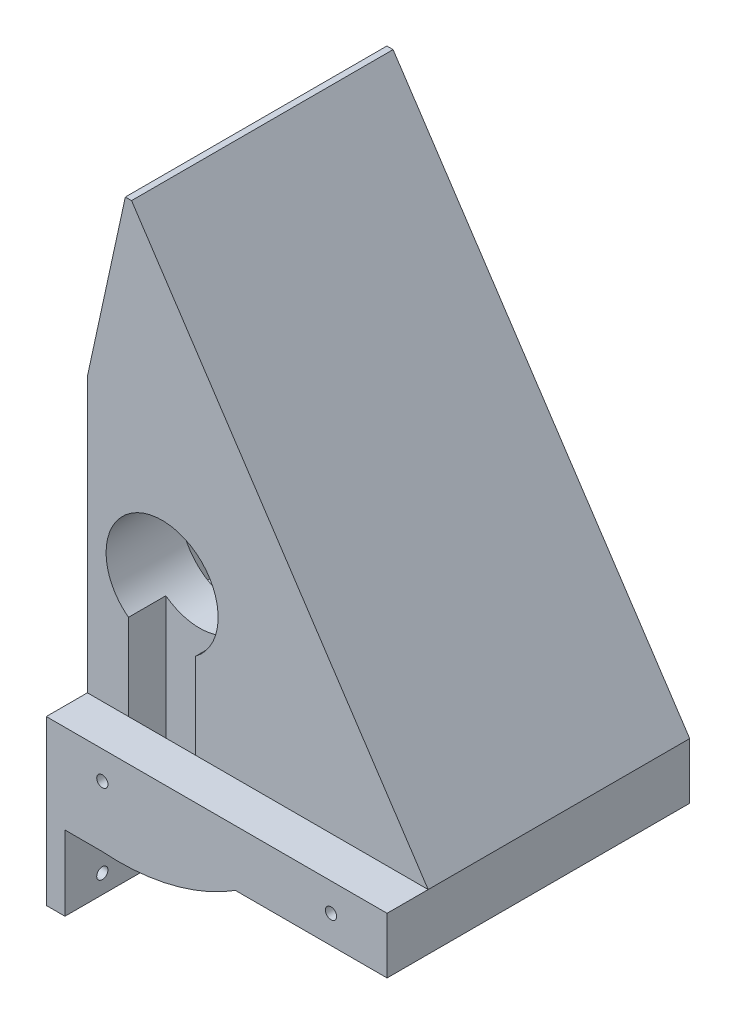
SolidWorks part; units mm, degrees
ref_plane "前视基准面" through (0, 0, 0) normal (0, 0, 1) x (1, 0, 0)
ref_plane "上视基准面" through (0, 0, 0) normal (0, 1, 0) x (1, 0, 0)
ref_plane "右视基准面" through (0, 0, 0) normal (1, 0, 0) x (0, 0, -1)
sketch "草图1" plane through (0, 0, 0) normal (1, 0, 0) x (0, 0, -1)
  line L0 (135, 0) -> (135, -170) construction
  line L1 (0, 0) -> (270, 0)
  line L2 (0, 0) -> (0, -100.2828)
  line L4 (270, 0) -> (270, -100.2828)
  line L5 (38.49, -136.6392) -> (62.3511, -70.3586) construction
  line L6 (21.17, -130.404) -> (127.5448, -168.6989) construction
  line L7 (142.4552, -168.6989) -> (248.83, -130.404) construction
  line L8 (58.2053, -81.8746) -> (-5.8219, -81.8746) construction
  line L9 (58.2053, -81.8746) -> (5.8219, -118.6911) construction
  line L10 (127.5448, -168.6989) -> (21.17, -130.404)
  line L11 (142.4552, -168.6989) -> (248.83, -130.404)
  line L12 (105.5031, -160.7639) -> (135, -78.8281) construction
  line L13 (135, -78.8281) -> (164.4969, -160.7639) construction
  arc A0 (0, -100.2828) -> (21.17, -130.404) centre (32.0136, -100.2828) ccw
  arc A1 (127.5448, -168.6989) -> (142.4552, -168.6989) centre (135, -147.9899) ccw
  arc A2 (270, -100.2828) -> (248.83, -130.404) centre (237.9864, -100.2828) cw
  dimension "D2" = 44.0202
  dimension "D3" = 170
  dimension "D1" = 270
  dimension "D4" = 32.0136
  dimension "D5" = 109.799
  dimension "D6" = 109.799
extrude "凸台-拉伸1" add sketch "草图1" along normal blind 30
sketch "草图2" plane through (30, 0, 0) normal (1, 0, 0) x (0, 0, -1)
  line L0 (135, 0) -> (135, -170) construction
  line L1 (270, 0) -> (0, 0) construction
  line L2 (135, -14.9009) -> (165, -14.9009) construction
  line L3 (165, 0) -> (165, -160.5828)
  line L4 (105, 0) -> (105, -160.5828)
  line L8 (0, 0) -> (0, -100.2828)
  line L9 (21.17, -130.404) -> (127.5448, -168.6989)
  line L10 (142.4552, -168.6989) -> (248.83, -130.404)
  line L11 (270, -100.2828) -> (270, 0)
  line L12 (270, 0) -> (0, 0)
  line L13 (0, 0) -> (0, -100.2828)
  line L14 (21.17, -130.404) -> (127.5448, -168.6989)
  line L15 (142.4552, -168.6989) -> (248.83, -130.404)
  line L16 (270, -100.2828) -> (270, 0)
  line L17 (270, 0) -> (0, 0)
  arc A0 (127.5448, -168.6989) -> (142.4552, -168.6989) centre (135, -147.9899) ccw construction
  arc A4 (0, -100.2828) -> (21.17, -130.404) centre (32.0136, -100.2828) ccw
  arc A5 (127.5448, -168.6989) -> (142.4552, -168.6989) centre (135, -147.9899) ccw
  arc A6 (248.83, -130.404) -> (270, -100.2828) centre (237.9864, -100.2828) ccw
  arc A7 (0, -100.2828) -> (21.17, -130.404) centre (32.0136, -100.2828) ccw
  arc A8 (127.5448, -168.6989) -> (142.4552, -168.6989) centre (135, -147.9899) ccw
  arc A9 (248.83, -130.404) -> (270, -100.2828) centre (237.9864, -100.2828) ccw
  line M12 (0, 0) -> (0, -100.2828)
  arc M13 (0, -100.2828) -> (21.17, -130.404) centre (32.0136, -100.2828) ccw
  line M14 (21.17, -130.404) -> (127.5448, -168.6989)
  line M16 (142.4552, -168.6989) -> (248.83, -130.404)
  arc M17 (248.83, -130.404) -> (270, -100.2828) centre (237.9864, -100.2828) ccw
  line M18 (270, -100.2828) -> (270, 0)
  line M19 (270, 0) -> (0, 0)
  dimension "D1" = 30
  dimension "D2" = 0
extrude "凸台-拉伸2" add sketch "草图2" along normal blind 210 contours L4 M19 M12 M13 M14 | L3 M19 M16 M17 M18
sketch "草图6" plane through (0, 0, -105) normal (0, 0, -1) x (-1, 0, 0)
  line L0 (-71.1167, 0) -> (-71.1167, -409.9146) construction
  line L8 (-30, -160.5828) -> (-30, 0)
  line L9 (-30, 0) -> (-240, 0)
  line L12 (-240, 0) -> (-240, -160.5828)
  line L13 (-240, -160.5828) -> (-30, -160.5828)
  line L15 (-30, -160.5828) -> (-30, 0)
  line L16 (-30, 0) -> (-240, 0)
  line L19 (-240, 0) -> (-240, -160.5828)
  line L20 (-240, -160.5828) -> (-30, -160.5828)
  dimension "D2" = 41.1167
  dimension "D1" = 0
sketch "草图8" plane through (240, 0, 0) normal (1, 0, 0) x (0, 0, -1)
  line L0 (105, 0) -> (105, -160.5828) construction
  line L1 (105, -60) -> (80, -60)
  line L2 (105, -60) -> (105, 60)
  line L3 (105, 60) -> (80, 60)
  line L4 (80, -60) -> (80, 60)
  line L5 (105, -60) -> (80, 60) construction
  line L6 (105, 60) -> (80, -60) construction
  line L7 (135, 0) -> (135, -208.0575) construction
  line L8 (165, 0) -> (105, 0) construction
  line L9 (105, 0) -> (0, 0) construction
  line L10 (165, 60) -> (190, -60) construction
  line L11 (165, -60) -> (190, 60) construction
  line L12 (190, -60) -> (190, 60)
  line L13 (165, 60) -> (190, 60)
  line L14 (165, -60) -> (165, 60)
  line L15 (165, -60) -> (190, -60)
  point P4 (92.5, 0)
  point P17 (177.5, 0)
  dimension "D1" = 25
  dimension "D2" = 60
  dimension "D3" = 60
extrude "凸台-拉伸5" add sketch "草图8" along normal blind 70
sketch "草图9" plane through (240, 0, 0) normal (-1, 0, 0) x (0, 0, 1)
  line L4 (-105, 60) -> (-105, 0)
  line L5 (-105, 0) -> (-80, 0)
  line L6 (-80, 0) -> (-80, 60)
  line L7 (-80, 60) -> (-105, 60)
  line L8 (-105, 60) -> (-105, 0)
  line L9 (-105, 0) -> (-80, 0)
  line L10 (-80, 0) -> (-80, 60)
  line L11 (-80, 60) -> (-105, 60)
  line L12 (-190, 0) -> (-165, 0)
  line L13 (-165, 0) -> (-165, 60)
  line L14 (-165, 60) -> (-190, 60)
  line L15 (-190, 60) -> (-190, 0)
  line L16 (-190, 0) -> (-165, 0)
  line L17 (-165, 0) -> (-165, 60)
  line L18 (-165, 60) -> (-190, 60)
  line L19 (-190, 60) -> (-190, 0)
  dimension "D1" = 0
  dimension "D2" = 0
extrude "凸台-拉伸6" add sketch "草图9" along normal blind 60
sketch "草图10" plane through (0, 0, -80) normal (0, 0, 1) x (1, 0, 0)
  line L0 (240, 0) -> (240, 31.0013) construction
  line L2 (180, 30) -> (270, 30) construction
  line L3 (180, 0) -> (180, 60) construction
  circle A0 centre (270, 30) radius 7.5
  dimension "D2" = 15
  dimension "D1" = 30
extrude "切除-拉伸3" cut sketch "草图10" against normal through all
sketch "草图11" plane through (0, 0, -105) normal (0, 0, -1) x (-1, 0, 0)
  line L0 (0, 0) -> (0, 80.2418) construction
  line L1 (-240, -160.5828) -> (-124.1295, -160.5828) construction
  line L2 (-124.1295, -160.5828) -> (-108.2032, -160.5828) construction
  line L3 (-30, 0) -> (-30, -40) construction
  line L4 (-30, -40) -> (-30, -160.5828)
  line L5 (-30, -160.5828) -> (-108.2032, -160.5828)
  circle A0 centre (-270, 30) radius 240 construction
  arc A1 (-108.2032, -160.5828) -> (-30, -40) centre (-270, 30) ccw
  circle A2 centre (-270, 30) radius 250 construction
  dimension "D1" = 480
  dimension "D2" = 10
extrude "凸台-拉伸7" add sketch "草图11" along normal blind 60
sketch "草图12" plane through (0, 0, -165) normal (0, 0, 1) x (1, 0, 0)
  line L0 (30, 0) -> (240, 0) construction
  line L1 (70, -45) -> (70, 0) construction
  line L4 (30, -160.5828) -> (30, 0) construction
  circle A0 centre (70, -45) radius 2.5
  dimension "D3" = 5
  dimension "D4" = 45
  dimension "D1" = 45
  dimension "D2" = 40
extrude "凸台-拉伸8" add sketch "草图12" along normal through all
sketch "草图13" plane through (0, 0, 0) normal (0, 1, 0) x (1, 0, 0)
  line L0 (0, 270) -> (0, 240.5719) construction
  line L1 (0, 270) -> (0, 0) construction
  line L2 (0, 240.5719) -> (0, 192.1942) construction
sketch "草图14" plane through (0, 0, 0) normal (0, 1, 0) x (1, 0, 0)
  line L0 (0, 250) -> (0, 200)
  line L1 (0, 250) -> (125, 250)
  line L2 (0, 200) -> (125, 200)
  line L3 (125, 250) -> (125, 200)
  line L4 (0, 270) -> (0, 0) construction
  line L5 (240, 270) -> (0, 270) construction
  line L6 (0, 135) -> (52.375, 135) construction
  line L7 (125, 20) -> (125, 70)
  line L8 (0, 70) -> (125, 70)
  line L9 (0, 20) -> (125, 20)
  line L10 (0, 20) -> (0, 70)
  dimension "D1" = 20
  dimension "D2" = 50
  dimension "D3" = 125
extrude "凸台-拉伸9" add sketch "草图14" along normal blind 120
sketch "草图15" plane through (0, 0, -20) normal (0, 0, 1) x (1, 0, 0)
  line L0 (0, 120) -> (0, 0) construction
  line L1 (0, 70) -> (70, 70)
  line L2 (0, 70) -> (0, 0)
  line L3 (0, 0) -> (70, 0)
  line L4 (70, 70) -> (70, 0)
  line L5 (0, 120) -> (125, 120) construction
  dimension "D1" = 70
  dimension "D2" = 70
  dimension "D3" = 50
extrude "切除-拉伸4" cut sketch "草图15" against normal blind 10
sketch "草图16" plane through (0, 0, -30) normal (0, 0, 1) x (1, 0, 0)
  line L0 (0, 35) -> (70, 35) construction
  line L1 (0, 70) -> (0, 0) construction
  line L2 (70, 0) -> (70, 70) construction
  line L3 (0, 35) -> (35, 35) construction
  line L4 (35, 70) -> (35, 0) construction
  line L5 (35, 35) -> (35, 15)
  line L6 (70, 70) -> (0, 70) construction
  line L7 (0, 35) -> (35, 35) construction
  line L8 (0, 0) -> (70, 0) construction
  line L9 (35, 35) -> (35, 55) construction
  line L10 (35, 55) -> (5, 55) construction
  line L11 (35, 35) -> (35, 55)
  line L12 (35, 55) -> (5, 55)
  line L13 (5, 55) -> (5, 15)
  line L14 (35, 15) -> (5, 15)
  point P21 (5, 35)
  dimension "D1" = 35
  dimension "D2" = 20
  dimension "D3" = 30
extrude "切除-拉伸5" cut sketch "草图16" against normal blind 20 contours L14 L5 L11 L12 L13
sketch "草图17" plane through (0, 0, -30) normal (0, 0, 1) x (1, 0, 0)
  line L0 (35, 35) -> (19.5, 34.5) construction
  line L1 (35, 55) -> (35, 15) construction
  circle A0 centre (19.5, 34.5) radius 43.4713
extrude "切除-拉伸6" cut sketch "草图17" along normal through all
sketch "草图18" plane through (0, 0, -20) normal (0, 0, 1) x (1, 0, 0)
  line L0 (0, 73.3523) -> (11.8199, 120) construction
  line L1 (0, 73.3523) -> (0, -4.3523) construction
  line L2 (0, 120) -> (125, 120) construction
  line L3 (11.8199, 120) -> (62.5, 43.3973) construction
  line L4 (62.5, 43.3973) -> (91.2115, 0) construction
  line L5 (11.8199, 120) -> (91.2115, 0)
  line L6 (91.2115, 0) -> (87.3179, 0)
  line L7 (70, 0) -> (125, 0) construction
  line L8 (87.3179, 0) -> (10.7417, 115.7446)
  line L9 (10.7417, 115.7446) -> (11.8199, 120)
  arc A0 (44.5899, 70) -> (0, 73.3523) centre (19.5, 34.5) ccw construction
extrude "凸台-拉伸10" add sketch "草图18" along normal blind 20
sketch "草图19" plane through (0, 0, -20) normal (0, 0, 1) x (1, 0, 0)
  line L0 (10.856, 115.5717) -> (11.8199, 120)
  line L1 (10.7417, 115.7446) -> (87.3179, 0) construction
  line L2 (11.8199, 120) -> (10.7417, 115.7446) construction
  line L3 (11.8199, 120) -> (125, 120) construction
  line L4 (11.8199, 120) -> (0, 65.6972)
  line L5 (0, 73.3523) -> (0, -4.3523) construction
  line L6 (0, 65.6972) -> (0, 73.3523)
  line L7 (0, 120) -> (0, 73.3523) construction
  line L8 (0, 73.3523) -> (10.1537, 120)
  line L9 (0, 120) -> (11.8199, 120) construction
  line L10 (10.1537, 120) -> (11.8199, 120)
  line L11 (10.1537, 120) -> (11.8199, 120)
  line M2 (38.6846, 73.509) -> (10.7417, 115.7446)
  line M3 (10.7417, 115.7446) -> (11.8199, 120)
  line M4 (11.8199, 120) -> (0, 120)
  arc M6 (0, 73.3523) -> (38.6846, 73.509) centre (19.5, 34.5) cw
extrude "凸台-拉伸11" add sketch "草图19" along normal blind 20 contours L8 L4 M6 M2 M3 M4
sketch "草图20" plane through (0, 0, -20) normal (0, 0, 1) x (1, 0, 0)
  line L3 (0, 120) -> (0, 73.3523)
  line L4 (0, 73.3523) -> (10.1537, 120)
  line L5 (10.1537, 120) -> (0, 120)
  line L6 (0, 120) -> (0, 73.3523)
  line L7 (0, 73.3523) -> (10.1537, 120)
  line L8 (10.1537, 120) -> (0, 120)
  dimension "D1" = 0
extrude "切除-拉伸7" cut sketch "草图20" against normal through all
sketch "草图22" plane through (0, 0, -20) normal (0, 0, 1) x (1, 0, 0)
  line L0 (44.8997, 70) -> (70, 32.0611)
  line L7 (70, 32.0611) -> (91.2115, 0)
  line L8 (91.2115, 0) -> (125, 0)
  line L9 (125, 0) -> (125, 120)
  line L10 (125, 120) -> (11.8199, 120)
  line L11 (11.8199, 120) -> (44.8997, 70)
  line L12 (44.8997, 70) -> (70, 70)
  line L13 (70, 70) -> (70, 32.0611)
  line L14 (70, 32.0611) -> (91.2115, 0)
  line L15 (91.2115, 0) -> (125, 0)
  line L16 (125, 0) -> (125, 120)
  line L17 (125, 120) -> (11.8199, 120)
  line L18 (11.8199, 120) -> (44.8997, 70)
  dimension "D1" = 0
extrude "切除-拉伸8" cut sketch "草图22" against normal through all
sketch "草图23" plane through (0, 0, 0) normal (0, 0, 1) x (1, 0, 0)
  line L0 (87.3179, 0) -> (91.2115, 0)
  line L10 (0, -4.3523) -> (0, -100.2828)
  line L11 (0, -100.2828) -> (240, -100.2828)
  line L12 (240, -100.2828) -> (240, 0)
  line L13 (240, 0) -> (91.2115, 0)
  line L14 (91.2115, 0) -> (11.8199, 120)
  line L15 (11.8199, 120) -> (10.1537, 120)
  line L16 (10.1537, 120) -> (0, 73.3523)
  line L17 (1.8573, 74.2302) -> (10.856, 115.5717)
  line L18 (10.856, 115.5717) -> (87.3179, 0)
  line L19 (87.3179, 0) -> (45.9481, 0)
  line L20 (0, -4.3523) -> (0, -100.2828)
  line L21 (0, -100.2828) -> (240, -100.2828)
  line L22 (240, -100.2828) -> (240, 0)
  line L23 (240, 0) -> (91.2115, 0)
  line L24 (91.2115, 0) -> (11.8199, 120)
  line L25 (11.8199, 120) -> (10.1537, 120)
  line L26 (10.1537, 120) -> (0, 73.3523)
  line L27 (1.8573, 74.2302) -> (10.856, 115.5717)
  line L28 (10.856, 115.5717) -> (87.3179, 0)
  line L29 (87.3179, 0) -> (45.9481, 0)
  arc A2 (0, -4.3523) -> (45.9481, 0) centre (19.5, 34.5) ccw
  arc A3 (1.8573, 74.2302) -> (0, 73.3523) centre (19.5, 34.5) ccw
  arc A4 (0, -4.3523) -> (45.9481, 0) centre (19.5, 34.5) ccw
  arc A5 (1.8573, 74.2302) -> (0, 73.3523) centre (19.5, 34.5) ccw
  line M18 (91.2115, 0) -> (11.8199, 120)
  line M19 (11.8199, 120) -> (10.1537, 120)
  line M20 (10.1537, 120) -> (0, 73.3523)
  arc M21 (0, 73.3523) -> (1.8573, 74.2302) centre (19.5, 34.5) cw
  line M22 (1.8573, 74.2302) -> (10.856, 115.5717)
  line M23 (10.856, 115.5717) -> (87.3179, 0)
  dimension "D1" = 0
extrude "凸台-拉伸19" add sketch "草图23" against normal up to next contours L0 M23 M18 M19 M20 M21 M22
sketch "草图24" plane through (0, 0, -20) normal (0, 0, 1) x (1, 0, 0)
  line L3 (87.3179, 0) -> (70, 26.1759)
  line L4 (70, 26.1759) -> (70, 0)
  line L5 (70, 0) -> (87.3179, 0)
  line L6 (87.3179, 0) -> (70, 26.1759)
  line L7 (70, 26.1759) -> (70, 0)
  line L8 (70, 0) -> (87.3179, 0)
  dimension "D1" = 0
extrude "凸台-拉伸20" add sketch "草图24" along normal up to vertex (20 mm away)
sketch "草图25" plane through (0, 0, -20) normal (0, 0, 1) x (1, 0, 0)
  line L2 (38.6846, 73.509) -> (10.856, 115.5717)
  line L3 (10.856, 115.5717) -> (1.8573, 74.2302)
  line L4 (38.6846, 73.509) -> (10.856, 115.5717)
  line L5 (10.856, 115.5717) -> (1.8573, 74.2302)
  arc A1 (38.6846, 73.509) -> (1.8573, 74.2302) centre (19.5, 34.5) ccw
  arc A2 (38.6846, 73.509) -> (1.8573, 74.2302) centre (19.5, 34.5) ccw
  dimension "D1" = 0
extrude "凸台-拉伸21" add sketch "草图25" along normal blind 20
sketch "草图26" plane through (0, 0, -250) normal (0, 0, -1) x (-1, 0, 0)
  line L10 (-70, 26.1759) -> (-38.6846, 73.509)
  line L11 (-70, 0) -> (-70, 26.1759)
  line L12 (-45.9481, 0) -> (-70, 0)
  line L13 (0, -100.2828) -> (0, -4.3523)
  line L14 (-240, -100.2828) -> (0, -100.2828)
  line L15 (-240, 0) -> (-240, -100.2828)
  line L16 (-91.2115, 0) -> (-240, 0)
  line L17 (-11.8199, 120) -> (-91.2115, 0)
  line L18 (-10.1537, 120) -> (-11.8199, 120)
  line L19 (0, 73.3523) -> (-10.1537, 120)
  line L20 (-70, 26.1759) -> (-38.6846, 73.509)
  line L21 (-70, 0) -> (-70, 26.1759)
  line L22 (-45.9481, 0) -> (-70, 0)
  line L23 (0, -100.2828) -> (0, -4.3523)
  line L24 (-240, -100.2828) -> (0, -100.2828)
  line L25 (-240, 0) -> (-240, -100.2828)
  line L26 (-91.2115, 0) -> (-240, 0)
  line L27 (-11.8199, 120) -> (-91.2115, 0)
  line L28 (-10.1537, 120) -> (-11.8199, 120)
  line L29 (0, 73.3523) -> (-10.1537, 120)
  arc A2 (0, 73.3523) -> (-38.6846, 73.509) centre (-19.5, 34.5) ccw
  arc A3 (-45.9481, 0) -> (0, -4.3523) centre (-19.5, 34.5) ccw
  arc A4 (0, 73.3523) -> (-38.6846, 73.509) centre (-19.5, 34.5) ccw
  arc A5 (-45.9481, 0) -> (0, -4.3523) centre (-19.5, 34.5) ccw
  dimension "D1" = 0
extrude "凸台-拉伸22" add sketch "草图26" along normal blind 20
sketch "草图27" plane through (0, 0, -270) normal (0, 0, -1) x (-1, 0, 0)
  line L4 (-38.6846, 73.509) -> (-70, 26.1759)
  line L5 (0, -4.3523) -> (0, 73.3523)
  line L6 (-70, 0) -> (-45.9481, 0)
  line L7 (-70, 26.1759) -> (-70, 0)
  line L8 (-38.6846, 73.509) -> (-70, 26.1759)
  line L9 (0, -4.3523) -> (0, 73.3523)
  line L10 (-70, 0) -> (-45.9481, 0)
  line L11 (-70, 26.1759) -> (-70, 0)
  arc A2 (0, 73.3523) -> (-38.6846, 73.509) centre (-19.5, 34.5) ccw
  arc A3 (-45.9481, 0) -> (0, -4.3523) centre (-19.5, 34.5) ccw
  arc A4 (0, 73.3523) -> (-38.6846, 73.509) centre (-19.5, 34.5) ccw
  arc A5 (-45.9481, 0) -> (0, -4.3523) centre (-19.5, 34.5) ccw
  dimension "D1" = 0
extrude "切除-拉伸9" cut sketch "草图27" against normal blind 30
sketch "草图29" plane through (0, 0, -70) normal (0, 0, -1) x (-1, 0, 0)
  line L0 (-5, 55) -> (-35, 15) construction
  line L1 (-5, 15) -> (-35, 55) construction
  line L4 (-35, 15) -> (-5, 15)
  line L5 (-35, 55) -> (-35, 15)
  line L6 (-5, 55) -> (-35, 55)
  line L7 (-5, 15) -> (-5, 55)
  line L8 (-35, 15) -> (-5, 15) construction
  line L9 (-35, 55) -> (-35, 15) construction
  line L10 (-5, 55) -> (-35, 55) construction
  line L11 (-5, 15) -> (-5, 55) construction
  circle A0 centre (-20, 35) radius 15
  dimension "D2" = 30
  dimension "D1" = 0
extrude "切除-拉伸11" cut sketch "草图29" against normal through all both and the other way through all
sketch "草图30" plane through (30, 0, 0) normal (1, 0, 0) x (0, 0, -1)
  line L3 (142.4552, -168.6989) -> (165, -160.5828)
  line L4 (165, -160.5828) -> (105, -160.5828)
  line L5 (105, -160.5828) -> (127.5448, -168.6989)
  line L6 (142.4552, -168.6989) -> (165, -160.5828)
  line L7 (165, -160.5828) -> (105, -160.5828)
  line L8 (105, -160.5828) -> (127.5448, -168.6989)
  arc A1 (127.5448, -168.6989) -> (142.4552, -168.6989) centre (135, -147.9899) ccw
  arc A2 (127.5448, -168.6989) -> (142.4552, -168.6989) centre (135, -147.9899) ccw
  dimension "D1" = 0
extrude "凸台-拉伸23" add sketch "草图30" along normal up to vertex (78.2032 mm away)
sketch "草图33" plane through (0, 0, -240) normal (0, 0, -1) x (-1, 0, 0)
  line L0 (-35, 15) -> (-5, 15) construction
  line L1 (-35, 55) -> (-35, 15) construction
  line L2 (-35, 55) -> (-5, 55) construction
  line L3 (-5, 55) -> (-5, 15) construction
  line L4 (-35, 15) -> (-5, 15)
  line L5 (-35, 55) -> (-35, 15)
  line L6 (-35, 55) -> (-5, 55)
  line L7 (-5, 55) -> (-5, 15)
extrude "切除-拉伸14" cut sketch "草图33" against normal blind 20
sketch "草图34" plane through (0, 0, -200) normal (0, 0, 1) x (1, 0, 0)
  line L0 (20, 50) -> (20, 2.4606) construction
  line L1 (11, 0) -> (11, 35.3006)
  line L2 (11, 0) -> (29, 0)
  line L3 (11, 35.3006) -> (29, 35.3006)
  line L4 (29, 0) -> (29, 35.3006)
  line L5 (11, 0) -> (29, 35.3006) construction
  line L6 (11, 35.3006) -> (29, 0) construction
  line L7 (0, 0) -> (91.2115, 0) construction
  arc A0 (35, 35) -> (5, 35) centre (20, 35) ccw construction
  point P7 (20, 17.6503)
  dimension "D1" = 18
extrude "切除-拉伸15" cut sketch "草图34" against normal blind 10
sketch "草图35" plane through (0, 0, -70) normal (0, 0, -1) x (-1, 0, 0)
  line L3 (-11, 0) -> (-11, 23)
  line L4 (-29, 0) -> (-11, 0)
  line L5 (-29, 23) -> (-29, 0)
  line L6 (-11, 0) -> (-11, 23)
  line L7 (-29, 0) -> (-11, 0)
  line L8 (-29, 23) -> (-29, 0)
  arc A1 (-29, 23) -> (-11, 23) centre (-20, 35) ccw
  arc A2 (-29, 23) -> (-11, 23) centre (-20, 35) ccw
  dimension "D1" = 0
extrude "切除-拉伸16" cut sketch "草图35" against normal blind 10
sketch "草图36" plane through (0, 0, 0) normal (-1, 0, 0) x (0, 0, 1)
  line L0 (-235.6917, -100.008) -> (-211.6417, -100.008) construction
  line L1 (-135, -147.9899) -> (-135, -104.794) construction
  line L2 (-34.3083, -100.008) -> (-58.3583, -100.008) construction
  circle A0 centre (-235.6917, -100.008) radius 15.9
  circle A1 centre (-34.3083, -100.008) radius 15.9
  ellipse E0 centre (-235.6917, -100.008) end of major axis (-211.6417, -100.008) minor radius 15.9
  ellipse E1 centre (-34.3083, -100.008) end of major axis (-58.3583, -100.008) minor radius 15.9
  dimension "D2" = 31.8
  dimension "D1" = 24.05
extrude "切除-拉伸17" cut sketch "草图36" against normal blind 4 contours A0 E0 | A0 | A0 E0 | E1 A1 | A1 | E1 A1
sketch "草图37" plane through (0, 0, 0) normal (0, 1, 0) x (1, 0, 0)
  line L0 (108.2032, 135) -> (337.5794, 135) construction
  line L1 (240, 80) -> (91.2115, 80)
  line L2 (240, 80) -> (240, 0)
  line L3 (240, 0) -> (91.2115, 0)
  line L4 (91.2115, 80) -> (91.2115, 0)
  line L5 (108.2032, 165) -> (108.2032, 105) construction
  line L6 (91.2115, 190) -> (91.2115, 270)
  line L7 (240, 270) -> (91.2115, 270)
  line L8 (240, 190) -> (240, 270)
  line L9 (240, 190) -> (91.2115, 190)
extrude "切除-拉伸18" cut sketch "草图37" against normal through all
sketch "草图38" plane through (0, 0, 0) normal (0, 0, 1) x (1, 0, 0)
  line L1 (70, -15) -> (76.2115, -15)
  line L2 (76.2115, -85.2828) -> (76.2115, -15)
  line L3 (15, -85.2828) -> (76.2115, -85.2828)
  line L4 (15, -23.7978) -> (15, -85.2828)
  line L5 (70, -15) -> (50.623, -15)
  line L6 (76.2115, -15) -> (91.2115, -15)
  line L7 (91.2115, -100.2828) -> (91.2115, 0) construction
  line L8 (91.2115, -15) -> (91.2115, -100.2828)
  line L9 (91.2115, -100.2828) -> (0, -100.2828) construction
  line L10 (91.2115, -100.2828) -> (15, -100.2828)
  line L11 (15, -100.2828) -> (15, -85.2828)
  line L12 (91.2115, -15) -> (91.2115, -100.2828)
  line L14 (91.2115, -151.5828) -> (91.2115, 0) construction
  line L15 (91.2115, -151.5828) -> (91.2115, 0)
  line L17 (91.2115, -151.5828) -> (15, -151.5828)
  line L18 (91.2115, -151.5828) -> (91.2115, -100.2828)
  line L19 (91.2115, -100.2828) -> (15, -100.2828)
  line L20 (15, -151.5828) -> (15, -100.2828)
  arc A0 (15, -23.7978) -> (50.623, -15) centre (19.5, 34.5) ccw
  line M12 (0, -100.2828) -> (91.2115, -100.2828)
  line M13 (91.2115, -100.2828) -> (91.2115, 0)
extrude "切除-拉伸20" cut sketch "草图38" against normal blind 80 contours L20 L17 L15 M12 | L11 L6 L2 L3 M12 M13 | A0 L4 L3 L2 L1 L5
sketch "草图39" plane through (0, 0, -270) normal (0, 0, -1) x (-1, 0, 0)
  line L10 (-180, 60) -> (-310, 60)
  line L11 (-180, 0) -> (-180, 60)
  line L12 (-91.2115, 0) -> (-180, 0)
  line L13 (-91.2115, -15) -> (-91.2115, 0)
  line L14 (-50.623, -15) -> (-91.2115, -15)
  line L15 (-15, -151.5828) -> (-15, -23.7978)
  line L16 (-240, -151.5828) -> (-15, -151.5828)
  line L17 (-240, -60) -> (-240, -151.5828)
  line L18 (-310, -60) -> (-240, -60)
  line L19 (-310, 60) -> (-310, -60)
  line L20 (-180, 60) -> (-310, 60)
  line L21 (-180, 0) -> (-180, 60)
  line L22 (-91.2115, 0) -> (-180, 0)
  line L23 (-91.2115, -15) -> (-91.2115, 0)
  line L24 (-50.623, -15) -> (-91.2115, -15)
  line L25 (-15, -151.5828) -> (-15, -23.7978)
  line L26 (-240, -151.5828) -> (-15, -151.5828)
  line L27 (-240, -60) -> (-240, -151.5828)
  line L28 (-310, -60) -> (-240, -60)
  line L29 (-310, 60) -> (-310, -60)
  arc A1 (-50.623, -15) -> (-15, -23.7978) centre (-19.5, 34.5) ccw
  arc A2 (-50.623, -15) -> (-15, -23.7978) centre (-19.5, 34.5) ccw
  dimension "D1" = 0
extrude "切除-拉伸21" cut sketch "草图39" against normal blind 81
sketch "草图40" plane through (0, 0, -80) normal (0, 0, 1) x (1, 0, 0)
  line L0 (98.1638, -151.5828) -> (30, -151.5828) construction
  line L1 (240, -151.5828) -> (15, -151.5828) construction
  line L2 (30, -151.5828) -> (30, -40) construction
  line L3 (74.6558, -141.5828) -> (40, -141.5828)
  line L4 (40, -141.5828) -> (40, -91.2436)
  arc A1 (30, -40) -> (108.2032, -160.5828) centre (270, 30) ccw construction
  arc A2 (30, -40) -> (98.1638, -151.5828) centre (270, 30) ccw construction
  arc A3 (40, -91.2436) -> (74.6558, -141.5828) centre (270, 30) ccw
  dimension "D1" = 10
extrude "切除-拉伸22" cut sketch "草图40" against normal through all
sketch "草图41" plane through (0, 0, 0) normal (0, 1, 0) x (1, 0, 0)
  line L0 (29, 60) -> (11, 60) construction
  line L1 (29, 60) -> (11, 60)
  line L2 (29, 60) -> (29, 70) construction
  line L3 (29, 60) -> (29, 70)
  line L4 (11, 60) -> (11, 70) construction
  line L5 (11, 60) -> (11, 70)
  line L6 (11, 70) -> (29, 70)
  line L7 (0, 135) -> (128.1299, 135) construction
  line L8 (0, 200) -> (0, 70) construction
  line L9 (11, 200) -> (29, 200)
  line L10 (11, 210) -> (11, 200)
  line L11 (29, 210) -> (29, 200)
  line L12 (29, 210) -> (11, 210)
extrude "切除-拉伸23" cut sketch "草图41" against normal blind 60
sketch "草图44" plane through (0, 60, 0) normal (0, 1, 0) x (1, 0, 0)
  line L0 (310, 80) -> (180, 80) construction
  line L1 (310, 189) -> (260, 189)
  line L2 (310, 189) -> (310, 80)
  line L3 (310, 80) -> (260, 80)
  line L4 (260, 189) -> (260, 80)
  dimension "D1" = 50
extrude "凸台-拉伸26" add sketch "草图44" along normal blind 15
sketch "草图45" plane through (0, -60, 0) normal (0, -1, 0) x (1, 0, 0)
  line L0 (310, -189) -> (240, -189) construction
  line L1 (310, -80) -> (260, -80)
  line L2 (310, -80) -> (310, -189)
  line L3 (310, -189) -> (260, -189)
  line L4 (260, -80) -> (260, -189)
  dimension "D1" = 50
extrude "凸台-拉伸27" add sketch "草图45" along normal blind 15
sketch "草图46" plane through (240, 0, 0) normal (1, 0, 0) x (0, 0, -1)
  line L0 (80, -151.5828) -> (105, -160.5828) construction
  line L1 (80, -151.5828) -> (105, -160.5828)
  line L2 (165, -160.5828) -> (190, -151.5828) construction
  line L3 (165, -160.5828) -> (189, -151.9428)
  line L4 (105, -160.5828) -> (165, -160.5828)
  line L5 (189, -60) -> (189, -151.5828) construction
  line L7 (80, -151.5828) -> (80, -130.5828)
  line L8 (80, -130.5828) -> (189, -130.5828)
  line L10 (189, -130.5828) -> (189, -151.9428)
  dimension "D2" = 30
extrude "凸台-拉伸28" add sketch "草图46" along normal blind 15
sketch "草图47" plane through (0, 0, -189) normal (0, 0, -1) x (-1, 0, 0)
  line L1 (-40, -91.2436) -> (-25, -91.2436)
  line L2 (-40, -91.2436) -> (-40, -141.5828)
  line L3 (-40, -141.5828) -> (-25, -141.5828)
  line L4 (-25, -91.2436) -> (-25, -141.5828)
  arc A0 (-74.6558, -141.5828) -> (-40, -91.2436) centre (-270, 30) ccw construction
  arc A1 (-74.6558, -141.5828) -> (-40, -91.2436) centre (-270, 30) ccw construction
  arc A2 (-108.2032, -160.5828) -> (-30, -40) centre (-270, 30) ccw construction
  arc A3 (-108.2032, -160.5828) -> (-30, -40) centre (-270, 30) ccw construction
  dimension "D1" = 15
extrude "切除-拉伸24" cut sketch "草图47" against normal up to surface (109 mm away) up to face at (51.0572, -125.1437, -80)
sketch "草图48" plane through (15, 0, 0) normal (1, 0, 0) x (0, 0, -1)
  line L1 (189, -23.7978) -> (189, 75)
  line L2 (189, 75) -> (0, 72.2962)
  line L3 (0, 0) -> (0, 120) construction
  line L5 (0, 120) -> (189, 120)
  line L6 (0, 120) -> (0, -180.7464)
  line L7 (0, -180.7464) -> (189, -180.7464)
  line L8 (0, 0) -> (70, 0)
  line L9 (270, -23.7978) -> (210, -23.7978)
  line L10 (210, -23.7978) -> (210, -60)
  line L11 (210, -60) -> (200, -60)
  line L12 (200, -60) -> (200, -23.7978)
  line L13 (200, -23.7978) -> (189, -23.7978)
  line L14 (189, -23.7978) -> (189, -151.5828)
  line L15 (189, -151.5828) -> (190, -151.5828)
  line L16 (190, -151.5828) -> (248.83, -130.404)
  line L17 (270, -100.2828) -> (270, -23.7978)
  line L23 (189, -23.7978) -> (189, -151.5828)
  line L24 (189, -151.5828) -> (190, -151.5828)
  line L27 (70, 0) -> (70, 120)
  line L28 (70, 120) -> (0, 120)
  line L29 (0, 120) -> (0, 0)
  line L30 (60, -60) -> (60, -23.7978)
  line L31 (60, -23.7978) -> (0, -23.7978)
  line L32 (0, -23.7978) -> (0, -100.2828)
  line L33 (21.17, -130.404) -> (80, -151.5828)
  line L34 (80, -151.5828) -> (80, -23.7978)
  line L35 (80, -23.7978) -> (70, -23.7978)
  line L36 (70, -23.7978) -> (70, -60)
  line L37 (70, -60) -> (60, -60)
  line L38 (60, -60) -> (60, -23.7978)
  line L39 (60, -23.7978) -> (0, -23.7978)
  line L40 (0, -23.7978) -> (0, -100.2828)
  line L41 (21.17, -130.404) -> (80, -151.5828)
  line L42 (80, -151.5828) -> (80, -23.7978)
  line L43 (80, -23.7978) -> (70, -23.7978)
  line L44 (70, -23.7978) -> (70, -60)
  line L45 (70, -60) -> (60, -60)
  line L46 (0, 0) -> (70, 0)
  line L47 (70, 0) -> (70, 120)
  line L48 (70, 120) -> (0, 120)
  line L49 (0, 120) -> (0, 0)
  line L50 (189, 120) -> (189, -180.7464)
  arc A1 (248.83, -130.404) -> (270, -100.2828) centre (237.9864, -100.2828) ccw
  arc A3 (0, -100.2828) -> (21.17, -130.404) centre (32.0136, -100.2828) ccw
  arc A4 (0, -100.2828) -> (21.17, -130.404) centre (32.0136, -100.2828) ccw
  line M29 (189, -23.7978) -> (189, -151.5828)
  dimension "D1" = 0
  dimension "D2" = 0
  dimension "D3" = 0
sketch "草图49" plane through (15, 0, 0) normal (1, 0, 0) x (0, 0, -1)
  line L4 (0, 120) -> (0, 72.2962)
  line L5 (0, 72.2962) -> (70, 73.2976)
  line L6 (70, 73.2976) -> (70, 120)
  line L7 (70, 120) -> (0, 120)
  line L8 (0, 120) -> (0, 72.2962)
  line L9 (270, -23.7978) -> (210, -23.7978)
  line L10 (210, -23.7978) -> (210, -60)
  line L11 (210, -60) -> (200, -60)
  line L12 (200, -60) -> (200, -23.7978)
  line L13 (200, -23.7978) -> (189, -23.7978)
  line L14 (189, -23.7978) -> (189, -151.5828)
  line L15 (189, -151.5828) -> (190, -151.5828)
  line L16 (190, -151.5828) -> (248.83, -130.404)
  line L17 (270, -100.2828) -> (270, -23.7978)
  line L18 (270, -23.7978) -> (210, -23.7978)
  line L19 (210, -23.7978) -> (210, -60)
  line L20 (210, -60) -> (200, -60)
  line L21 (200, -60) -> (200, -23.7978)
  line L22 (200, -23.7978) -> (189, -23.7978)
  line L23 (189, -23.7978) -> (189, -151.5828)
  line L24 (189, -151.5828) -> (190, -151.5828)
  line L25 (190, -151.5828) -> (248.83, -130.404)
  line L26 (270, -100.2828) -> (270, -23.7978)
  line L27 (0, 72.2962) -> (70, 73.2976)
  line L28 (70, 73.2976) -> (70, 120)
  line L29 (70, 120) -> (0, 120)
  arc A1 (248.83, -130.404) -> (270, -100.2828) centre (237.9864, -100.2828) ccw
  arc A2 (248.83, -130.404) -> (270, -100.2828) centre (237.9864, -100.2828) ccw
  dimension "D1" = 0
  dimension "D2" = 0
sketch "草图51" plane through (240, 0, 0) normal (1, 0, 0) x (0, 0, -1)
  line L3 (190, -151.5828) -> (189, -151.5828)
  line L4 (189, -151.5828) -> (189, -151.9428)
  line L5 (189, -151.9428) -> (190, -151.5828)
  line L6 (190, -151.5828) -> (189, -151.5828)
  line L7 (189, -151.5828) -> (189, -151.9428)
  line L8 (189, -151.9428) -> (190, -151.5828)
  dimension "D1" = 0
extrude "切除-拉伸27" cut sketch "草图51" against normal through all both and the other way through all
extrude "切除-拉伸28" cut sketch "草图48" against normal through all both and the other way through all contours L2 L47 L5 L6 | L50 L5 L47 L2 | L46 L47 L2 L6 | A4 L6 L7 L50 L1 L2 L47 L46 L39 L38 L45 L44 L43 L42 L41 M29 | L6 A4 L41 L42 L43 L44 L45 L38 L39
sketch "草图55" plane through (15, 0, 0) normal (1, 0, 0) x (0, 0, -1)
  line L0 (189, -23.7978) -> (270, -23.7978)
  line L1 (189, -23.7978) -> (189, -163.3862)
  line L2 (270, -23.7978) -> (270, -163.3862)
  line L3 (189, -163.3862) -> (270, -163.3862)
sketch "草图56" plane through (0, 0, 0) normal (-1, 0, 0) x (0, 0, 1)
  line L1 (-270, -23.7978) -> (-189, -23.7978)
  line L2 (-270, -23.7978) -> (-270, -163.3862)
  line L3 (-270, -163.3862) -> (-189, -163.3862)
  line L4 (-189, -23.7978) -> (-189, -163.3862)
extrude "切除-拉伸29" cut sketch "草图56" against normal blind 15 and the other way through all
sketch "草图57" plane through (0, -23.7978, 0) normal (0, -1, 0) x (1, 0, 0)
  line L0 (0, -270) -> (15, -270) construction
  line L1 (0, -189) -> (5, -189)
  line L2 (0, -189) -> (0, -270)
  line L3 (0, -270) -> (5, -270)
  line L4 (5, -189) -> (5, -270)
  dimension "D1" = 5
extrude "凸台-拉伸30" add sketch "草图57" along normal blind 20
sketch "草图58" plane through (5, 0, 0) normal (1, 0, 0) x (0, 0, -1)
  line L0 (270, -33.7978) -> (189, -33.7978) construction
  line L1 (270, -43.7978) -> (270, -23.7978) construction
  line L2 (189, -43.7978) -> (189, -23.7978) construction
  line L3 (270, -33.7978) -> (270, -43.7978) construction
  line L4 (270, -38.7978) -> (260, -38.7978) construction
  line L5 (229.5, -33.7978) -> (229.5, -60.6686) construction
  circle A0 centre (260, -38.7978) radius 1.5
  circle A1 centre (199, -38.7978) radius 1.5
  dimension "D2" = 3
  dimension "D1" = 10
extrude "切除-拉伸30" cut sketch "草图58" against normal blind 20
sketch "草图59" plane through (0, 0, -189) normal (0, 0, 1) x (1, 0, 0)
  line L0 (91.2115, -7.5) -> (0, -7.5) construction
  line L1 (91.2115, -15) -> (91.2115, 0) construction
  line L2 (0, 0) -> (0, -43.7978) construction
  line L3 (0, -10.3034) -> (15, -10.3034) construction
  line L4 (91.2115, -7.5) -> (76.2115, -7.5) construction
  circle A0 centre (15, -7.5) radius 1.5
  circle A1 centre (76.2115, -7.5) radius 1.5
  dimension "D2" = 3
  dimension "D5" = 3
  dimension "D1" = 15
  dimension "D3" = 15
  dimension "D4" = 15
extrude "切除-拉伸31" cut sketch "草图59" against normal blind 10
